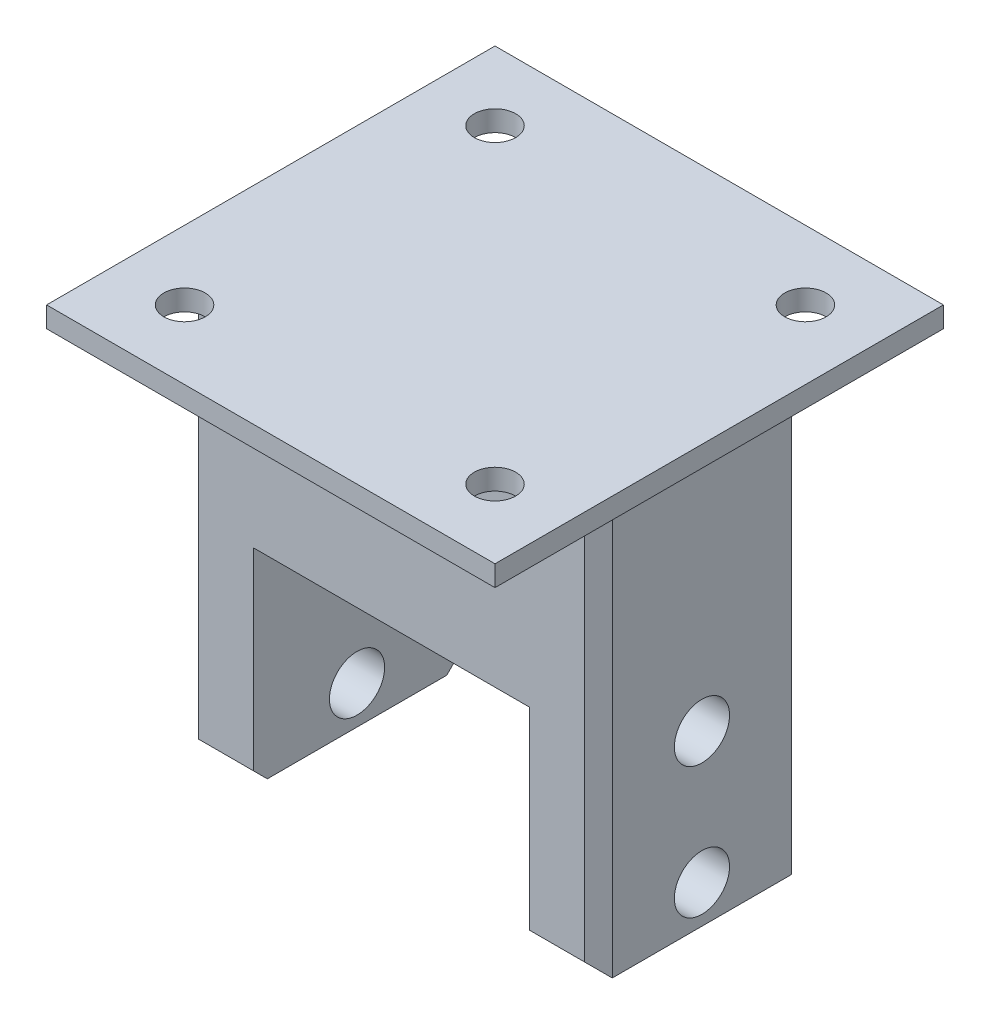
SolidWorks part; units mm, degrees
ref_plane "前视" through (0, 0, 0) normal (0, 0, 1) x (1, 0, 0)
ref_plane "上视" through (0, 0, 0) normal (0, 1, 0) x (1, 0, 0)
ref_plane "右视" through (0, 0, 0) normal (1, 0, 0) x (0, 0, -1)
sketch "草图1" plane through (0, 0, 0) normal (0, 0, 1) x (1, 0, 0)
  line L0 (0, 30) -> (0, -33.7174) construction
  line L1 (-30, -30) -> (-20, -30)
  line L2 (-20, -30) -> (-20, 0)
  line L3 (-20, 0) -> (20, 0)
  line L4 (-30, -30) -> (-30, 30)
  line L5 (-30, 30) -> (30, 30)
  line L6 (30, -30) -> (30, 30)
  line L7 (20, -30) -> (20, 0)
  line L8 (30, -30) -> (20, -30)
  point P10 (0, 0)
  dimension "D1" = 40
  dimension "D2" = 10
  dimension "D3" = 30
  dimension "D4" = 60
extrude "凸台-拉伸1" add sketch "草图1" along normal blind 30
sketch "草图2" plane through (-30, 0, 0) normal (-1, 0, 0) x (0, 0, 1)
  line L0 (15, -30) -> (15, 3.8379) construction
  line L1 (30, -30) -> (0, -30) construction
  circle A0 centre (15, -5.5) radius 4
  circle A1 centre (15, -24.5) radius 4
  dimension "D1" = 8
  dimension "D2" = 8
  dimension "D3" = 5.5
  dimension "D4" = 19
extrude "切除-拉伸1" cut sketch "草图2" against normal through all
sketch "草图3" plane through (0, 30, 0) normal (0, 1, 0) x (1, 0, 0)
  line L1 (32.5, 17.5) -> (-32.5, 17.5)
  line L2 (32.5, 17.5) -> (32.5, -47.5)
  line L3 (32.5, -47.5) -> (-32.5, -47.5)
  line L4 (-32.5, 17.5) -> (-32.5, -47.5)
  line L5 (32.5, 17.5) -> (-32.5, -47.5) construction
  line L6 (32.5, -47.5) -> (-32.5, 17.5) construction
  circle A0 centre (22.5, -37.5) radius 3
  circle A1 centre (-22.5, -37.5) radius 3
  circle A2 centre (-22.5, 7.5) radius 3
  circle A3 centre (22.5, 7.5) radius 3
  point P0 (0, -15)
  point P16 (0, -15)
  dimension "D2" = 6
  dimension "D1" = 65
  dimension "D3" = 10
  dimension "D4" = 4
extrude "凸台-拉伸2" add sketch "草图3" along normal blind 3
chamfer "倒角2" distance 2 angle 45 10 edges at (30, 0, 0) (30, 0, 30) (-30, 0, 30) (-30, 0, 0) (25, -30, 0) (30, -30, 15) (25, -30, 30) (-25, -30, 30) (-30, -30, 15) (-25, -30, 0)
